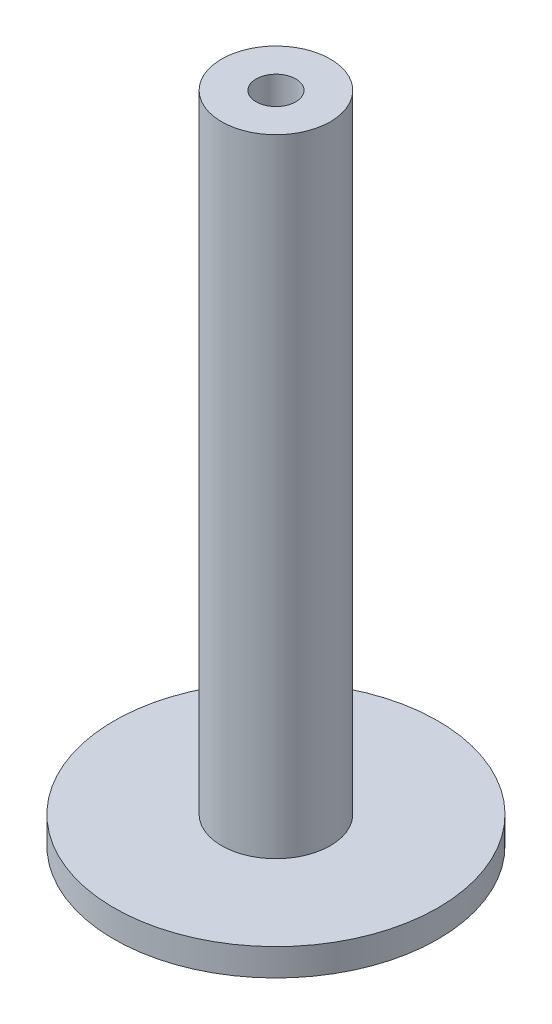
SolidWorks part; units mm, degrees
ref_plane "Piano frontale" through (0, 0, 0) normal (0, 0, 1) x (1, 0, 0)
ref_plane "Piano superiore" through (0, 0, 0) normal (0, 1, 0) x (1, 0, 0)
ref_plane "Piano destro" through (0, 0, 0) normal (1, 0, 0) x (0, 0, -1)
sketch "Schizzo1" plane through (0, 0, 0) normal (0, 1, 0) x (1, 0, 0)
  circle A0 centre (0, 0) radius 0.95
  dimension "D1" = 1.9
extrude "Estrusione-Sottile2" add sketch "Schizzo1" along normal blind 1.3 thin
sketch "Schizzo3" plane through (0, 1.3, 0) normal (0, 1, 0) x (1, 0, 0)
  circle A0 centre (0, 0) radius 0.95
extrude "Estrusione-Sottile3" add sketch "Schizzo3" along normal blind 30 thin
